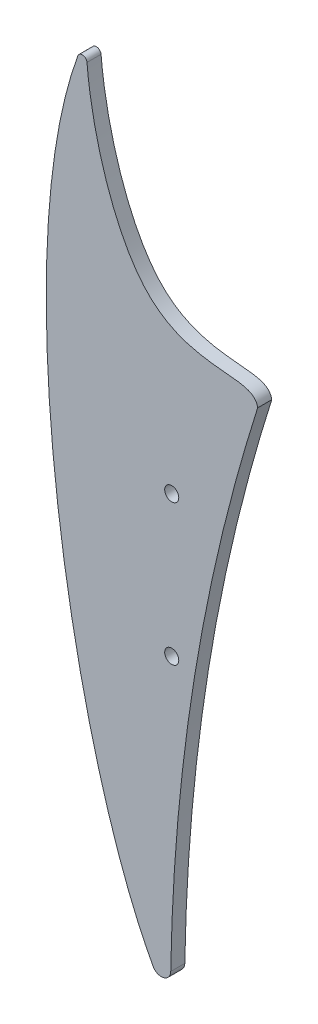
SolidWorks part; units mm, degrees
ref_plane "Front Plane" through (0, 0, 0) normal (0, 0, 1) x (1, 0, 0)
ref_plane "Top Plane" through (0, 0, 0) normal (0, 1, 0) x (1, 0, 0)
ref_plane "Right Plane" through (0, 0, 0) normal (1, 0, 0) x (0, 0, -1)
sketch "Sketch1" plane through (0, 0, 0) normal (0, 0, 1) x (1, 0, 0)
  line L0 (0, 0) -> (18.5792, 120) construction
  line L1 (18.5792, 120) -> (-18.0328, 170) construction
  line L2 (-18.0328, 170) -> (0, 0) construction
  circle A1 centre (0.27, 65) radius 1.5
  circle A2 centre (0.27, 95) radius 1.5
  spline S0 degree 2 poles (0, 0) (0.039, 61.6049) (18.5792, 120) knots 0 0 0 1 1 1
  spline S1 degree 3 poles (0, 0) (-19.4773, 25.8683) (-37.6291, 125.9869) (-18.0328, 170) knots 0 0 0 0 1 1 1 1
  spline S2 degree 3 poles (-18.0328, 170) (-17.7423, 156.2851) (-6.5388, 115.0231) (17.7206, 125.5987) (18.5792, 120) knots 0 0 0 0 0.447403 1 1 1 1
  spline S3 degree 1 poles (-4.5209, 19.6095) (12.6954, 117.9338) knots 0 0 1 1 construction
  spline S4 degree 1 poles (-19.3284, 147.0543) (12.6954, 117.9338) knots 0 0 1 1 construction
  spline S5 degree 1 poles (-4.5209, 19.6095) (-19.3284, 147.0543) knots 0 0 1 1 construction
  spline S6 degree 2 poles (-4.5209, 19.6095) (-4.2434, 25.338) (-2.929, 42.4419) (0.1093, 65.0278) (6.3437, 97.272) (12.6954, 117.9338) knots 0.157841 0.157841 0.157841 0.250447 0.43566 0.620872 0.969754 0.969754 0.969754 construction
  spline S7 degree 3 poles (12.6954, 117.9338) (12.4493, 117.9604) (11.9758, 118.0078) (10.8764, 118.1101) (9.3483, 118.2521) (7.2858, 118.4969) (4.2977, 118.9963) (0.2007, 120.0958) (-4.0827, 122.2736) (-7.3603, 124.8553) (-10.4553, 128.0579) (-13.6893, 132.8679) (-16.3481, 138.4774) (-18.1547, 143.2927) (-18.9575, 145.7999) (-19.3284, 147.0543) knots 0.216475 0.216475 0.216475 0.216475 0.234514 0.252553 0.28863 0.324708 0.360786 0.432941 0.505097 0.541174 0.577252 0.649407 0.721563 0.757641 0.793718 0.793718 0.793718 0.793718 construction
  spline S8 degree 3 poles (-19.3284, 147.0543) (-19.529, 145.8377) (-19.8922, 143.4215) (-20.5151, 138.3882) (-21.0818, 131.872) (-21.4424, 123.7235) (-21.5146, 112.5269) (-20.8789, 98.0739) (-19.0891, 80.5406) (-16.8593, 66.2152) (-14.7053, 55.1924) (-12.9236, 47.211) (-10.9946, 39.5826) (-9.2811, 33.5763) (-7.8573, 29.0169) (-6.7655, 25.7281) (-5.8392, 23.107) (-5.0873, 21.0795) (-4.7126, 20.1014) (-4.5209, 19.6095) knots 0.161502 0.161502 0.161502 0.161502 0.183202 0.204902 0.248301 0.291701 0.335101 0.4219 0.508699 0.595498 0.638898 0.682298 0.725697 0.769097 0.790797 0.812496 0.834196 0.845046 0.855896 0.855896 0.855896 0.855896 construction
  point P14 (0, 0)
  dimension "D2" = 30
  dimension "D1" = 120
  dimension "D3" = 50
extrude "Boss-Extrude1" add sketch "Sketch1" along normal blind 3
fillet "Fillet1" radius 1 1 edges at (-18.0328, 170, 1.5)
fillet "Fillet2" radius 2 1 edges at (0, 0, 1.5)
